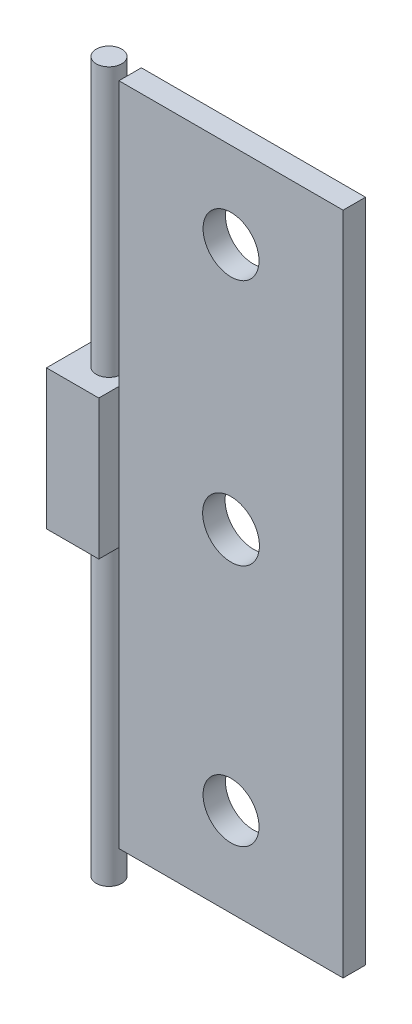
SolidWorks part; units mm, degrees
ref_plane "Alzado" through (0, 0, 0) normal (0, 0, 1) x (1, 0, 0)
ref_plane "Planta" through (0, 0, 0) normal (0, 1, 0) x (1, 0, 0)
ref_plane "Vista lateral" through (0, 0, 0) normal (1, 0, 0) x (0, 0, -1)
sketch "Croquis1" plane through (0, 0, 0) normal (0, 0, 1) x (1, 0, 0)
  line L1 (-15, 44.5) -> (15, 44.5)
  line L2 (-15, 44.5) -> (-15, -44.5)
  line L3 (-15, -44.5) -> (15, -44.5)
  line L4 (15, 44.5) -> (15, -44.5)
  line L5 (-15, 44.5) -> (15, -44.5) construction
  line L6 (-15, -44.5) -> (15, 44.5) construction
  point P0 (0, 0)
  dimension "D1" = 89
  dimension "D2" = 30
extrude "Saliente-Extruir1" add sketch "Croquis1" along normal blind 3
sketch "Croquis2" plane through (0, 0, 3) normal (0, 0, 1) x (1, 0, 0)
  circle A0 centre (0, 0) radius 3.8009
  circle A1 centre (0, 32.9973) radius 3.743
  circle A2 centre (0, -32.6033) radius 3.743
extrude "Cortar-Extruir1" cut sketch "Croquis2" against normal blind 3
sketch "Croquis3" plane through (-15, 0, 0) normal (-1, 0, 0) x (0, 0, 1)
  line L1 (-1.5245, 9.0748) -> (5.699, 9.0748)
  line L2 (-1.5245, 9.0748) -> (-1.5245, -9.5928)
  line L3 (-1.5245, -9.5928) -> (5.699, -9.5928)
  line L4 (5.699, 9.0748) -> (5.699, -9.5928)
  line L5 (-1.5245, 9.0748) -> (5.699, -9.5928) construction
  line L6 (-1.5245, -9.5928) -> (5.699, 9.0748) construction
  point P0 (2.0872, -0.259)
extrude "Saliente-Extruir2" add sketch "Croquis3" along normal blind 7
sketch "Croquis4" plane through (0, 9.0748, 0) normal (0, 1, 0) x (1, 0, 0)
  circle A0 centre (-17.9105, -1.4221) radius 1.7075
extrude "Saliente-Extruir3" add sketch "Croquis4" along normal blind 36 and the other way blind 59
